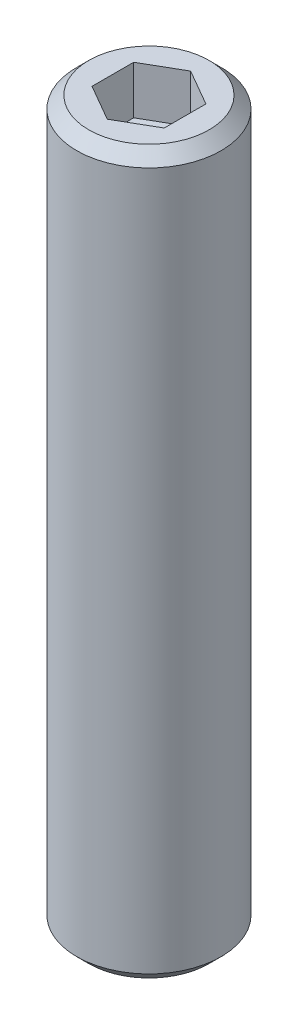
SolidWorks part; units mm, degrees
material "Cast Alloy Steel"
ref_plane "Front Plane" through (0, 0, 0) normal (0, 0, 1) x (1, 0, 0)
ref_plane "Top Plane" through (0, 0, 0) normal (0, 1, 0) x (1, 0, 0)
ref_plane "Right Plane" through (0, 0, 0) normal (1, 0, 0) x (0, 0, -1)
sketch "Sketch1" plane through (0, 0, 0) normal (0, 1, 0) x (1, 0, 0)
  circle A0 centre (0, 0) radius 3
  dimension "D1" = 6
extrude "Boss-Extrude1" add sketch "Sketch1" against normal blind 30
sketch "Sketch2" plane through (0, 0, 0) normal (0, 1, 0) x (1, 0, 0)
  line L1 (0, 1.7321) -> (-1.5, 0.866)
  line L2 (-1.5, 0.866) -> (-1.5, -0.866)
  line L3 (-1.5, -0.866) -> (0, -1.7321)
  line L4 (0, -1.7321) -> (1.5, -0.866)
  line L5 (1.5, -0.866) -> (1.5, 0.866)
  line L6 (1.5, 0.866) -> (0, 1.7321)
  circle A0 centre (0, 0) radius 1.5 construction
  dimension "D1" = 3
extrude "Cut-Extrude1" cut sketch "Sketch2" against normal blind 2
chamfer "Chamfer1" distance 0.5 angle 45 2 edges at (0, -30, 3) (0, 0, 3)
